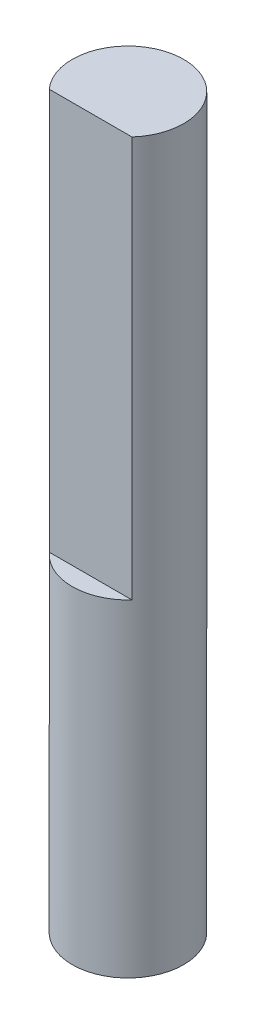
SolidWorks part; units mm, degrees
ref_plane "Front Plane" through (0, 0, 0) normal (0, 0, 1) x (1, 0, 0)
ref_plane "Top Plane" through (0, 0, 0) normal (0, 1, 0) x (1, 0, 0)
ref_plane "Right Plane" through (0, 0, 0) normal (1, 0, 0) x (0, 0, -1)
sketch "Sketch1" plane through (0, 0, 0) normal (0, 1, 0) x (1, 0, 0)
  circle A0 centre (0, 0) radius 2.5019
  dimension "D1" = 5.0038
extrude "Boss-Extrude1" add sketch "Sketch1" along normal blind 14.7
sketch "Sketch2" plane through (0, 14.7, 0) normal (0, 1, 0) x (1, 0, 0)
  line L0 (-1.8555, -1.6783) -> (1.8555, -1.6783)
  circle A0 centre (0, 0) radius 2.5019 construction
  arc A1 (1.8555, -1.6783) -> (-1.8555, -1.6783) centre (0, 0) ccw
  dimension "D1" = 1.8555
extrude "Boss-Extrude2" add sketch "Sketch2" along normal blind 18
